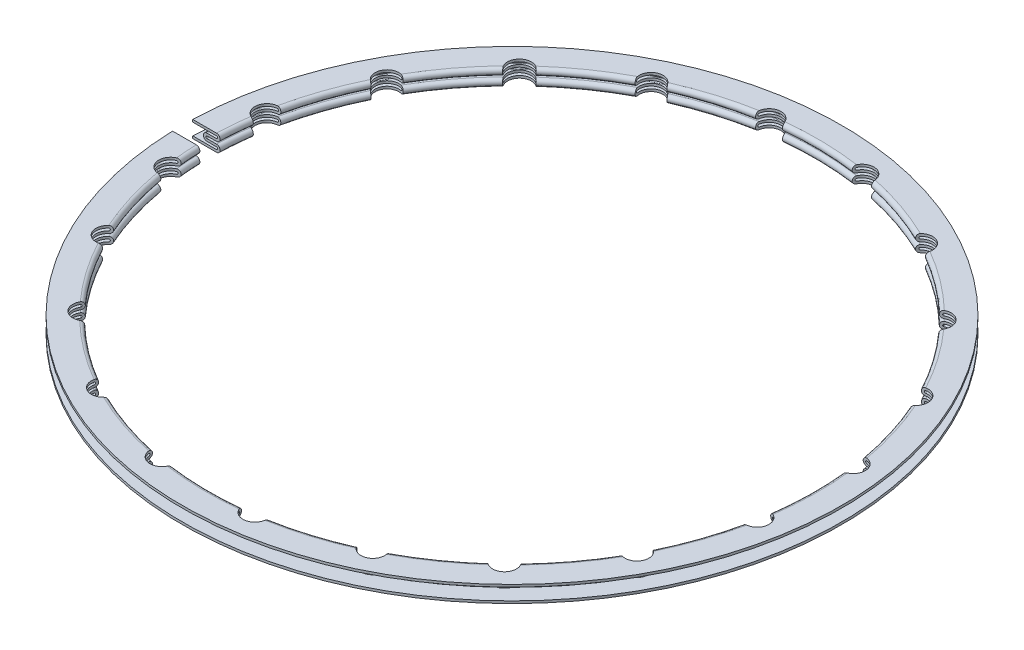
SolidWorks part; units mm, degrees
material "AISI 1045 Steel, cold drawn"
ref_plane "Front Plane" through (0, 0, 0) normal (0, 0, 1) x (1, 0, 0)
ref_plane "Top Plane" through (0, 0, 0) normal (0, 1, 0) x (1, 0, 0)
ref_plane "Right Plane" through (0, 0, 0) normal (1, 0, 0) x (0, 0, -1)
sketch "Sketch1" plane through (0, 0, 0) normal (0, 0, 1) x (1, 0, 0)
  line L0 (0, 0) -> (0, 6.3561) construction
  line L1 (35.2425, 0) -> (32.7025, 0)
  line L2 (32.7025, 0.508) -> (33.7185, 0.508)
  line L3 (33.7185, 1.016) -> (32.7025, 1.016)
  line L4 (32.7025, 1.524) -> (35.2425, 1.524)
  arc A0 (32.7025, 0) -> (32.7025, 0.508) centre (32.7025, 0.254) cw
  arc A1 (33.7185, 0.508) -> (33.7185, 1.016) centre (33.7185, 0.762) ccw
  arc A2 (32.7025, 1.016) -> (32.7025, 1.524) centre (32.7025, 1.27) cw
  dimension "D2" = 0.254
  dimension "D3" = 70.485
  dimension "D1" = 2.54
  dimension "D4" = 1.524
revolve "Revolve-Thin1" add sketch "Sketch1" angle 360 about L0
sketch "Sketch2" plane through (0, 1.651, 0) normal (0, 1, 0) x (1, 0, 0)
  line L0 (0, 0) -> (0, 42.2071) construction
  line L1 (0, 0) -> (5.6126, 31.8305) construction
  circle A0 centre (5.6126, 31.8305) radius 1.27
  circle A1 centre (0, 0) radius 32.3215 construction
  dimension "D1" = 2.54
  dimension "D2" = 10
extrude "Cut-Extrude1" cut sketch "Sketch2" against normal through all
pattern_circular "CirPattern1" count 20 over 360 about axis through (0, 0, 0) along (0, 1, 0) of "Cut-Extrude1"
sketch "Sketch3" plane through (0, 1.651, 0) normal (0, 1, 0) x (1, 0, 0)
  line L1 (-32.3035, -1.0795) -> (-35.2425, -1.0795)
  line L2 (-32.3035, -1.0795) -> (-32.3035, 1.0795)
  line L3 (-32.3035, 1.0795) -> (-35.2425, 1.0795)
  line L4 (-35.2425, -1.0795) -> (-35.2425, 1.0795)
  line L5 (-33.773, 1.0795) -> (-33.773, -1.0795) construction
  line L6 (-32.3035, 0) -> (-35.2425, 0) construction
  arc A0 (-32.0264, 4.3578) -> (-32.159, -3.2374) centre (0, 0) ccw construction
  circle A3 centre (0, 0) radius 35.2425 construction
  point P0 (-33.773, 0)
  dimension "D1" = 2.159
extrude "Cut-Extrude2" cut sketch "Sketch3" against normal through all
